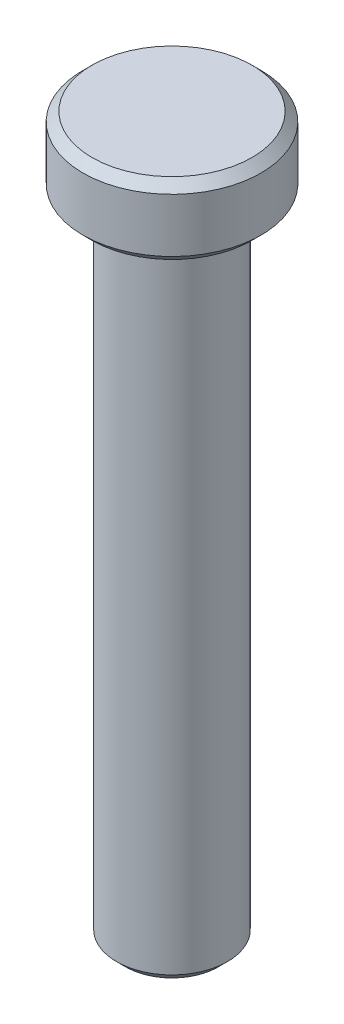
SolidWorks part; units mm, degrees
ref_plane "Front Plane" through (0, 0, 0) normal (0, 0, 1) x (1, 0, 0)
ref_plane "Top Plane" through (0, 0, 0) normal (0, 1, 0) x (1, 0, 0)
ref_plane "Right Plane" through (0, 0, 0) normal (1, 0, 0) x (0, 0, -1)
sketch "Sketch1" plane through (0, 0, 0) normal (0, 1, 0) x (1, 0, 0)
  circle A0 centre (0, 0) radius 3.937
  dimension "D1" = 7.874
extrude "Boss-Extrude1" add sketch "Sketch1" along normal mid plane 3.175
sketch "Sketch2" plane through (0, -1.5875, 0) normal (0, -1, 0) x (1, 0, 0)
  circle A0 centre (0, 0) radius 2.4511
  dimension "D1" = 4.9022
extrude "Boss-Extrude2" add sketch "Sketch2" along normal blind 28.575
chamfer "Chamfer1" distance 0.3969 angle 45 3 edges at (0, -30.1625, -2.4511) (0, 1.5875, 3.937) (0, -1.5875, 3.937)
